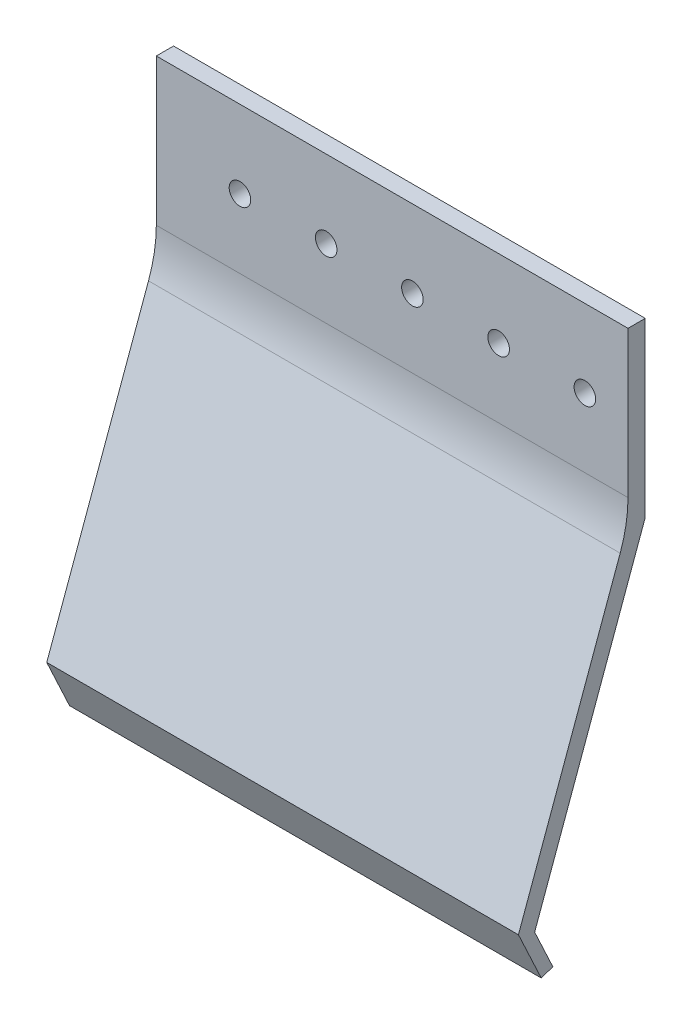
SolidWorks part; units mm, degrees
ref_plane "Front Plane" through (0, 0, 0) normal (0, 0, 1) x (1, 0, 0)
ref_plane "Top Plane" through (0, 0, 0) normal (0, 1, 0) x (1, 0, 0)
ref_plane "Right Plane" through (0, 0, 0) normal (1, 0, 0) x (0, 0, -1)
sketch "Sketch1" plane through (0, 0, 0) normal (0, 0, 1) x (1, 0, 0)
  line L0 (-72.2, 72.2) -> (37.2, 72.2)
  line L5 (-57.2, 57.2) -> (22.2, 57.2)
  line L6 (-57.2, 57.2) -> (-57.2, -22.2)
  line L7 (-57.2, -22.2) -> (22.2, -22.2)
  line L8 (22.2, 57.2) -> (22.2, -22.2)
  line L9 (37.2, 72.2) -> (37.2, -37.2)
  line L10 (-72.2, -37.2) -> (37.2, -37.2)
  line L11 (-72.2, 72.2) -> (-72.2, -37.2)
  circle A0 centre (-52.5, 52.5) radius 1.5
  circle A1 centre (-17.5, 52.5) radius 1.5
  circle A2 centre (17.5, 52.5) radius 1.5
  circle A3 centre (-52.5, 17.5) radius 1.5
  circle A4 centre (-17.5, 17.5) radius 1.5
  circle A5 centre (17.5, 17.5) radius 1.5
  circle A6 centre (17.5, -17.5) radius 1.5
  circle A7 centre (-17.5, -17.5) radius 1.5
  circle A8 centre (-52.8099, -17.8099) radius 1.5
  circle A9 centre (-35, 35) radius 6
  circle A10 centre (0, 35) radius 6
  circle A11 centre (0, 0) radius 6
  circle A12 centre (-35, 0) radius 6
  point P49 (-17.5, 17.5)
  dimension "D1" = 15
  dimension "D2" = 4
extrude "Boss-Extrude1" add sketch "Sketch1" along normal blind 8 contours L8 L5 L6 L7 A12 A11 A10 A9 A8 A7 A6 A5 A4 A3 A2 A1 A0 | L0 L11 L10 L9 L5 L8 L7 L6
sketch "Sketch2" plane through (37.2, 0, 0) normal (1, 0, 0) x (0, 0, -1)
  line L0 (-8, 72.2) -> (-33.6515, 1.7231)
  line L1 (-153.8845, -135.915) -> (25.507, -52.2634) construction
  line L2 (-8, -37.2) -> (0, -37.2) construction
  line L3 (-8, 72.2) -> (-8, 112.2)
  line L4 (-12, 72.9053) -> (-12, 112.2)
  line L5 (-12, 72.9053) -> (-37.4103, 3.0911)
  line L6 (-37.4103, 3.0911) -> (-32.1276, -8.2377)
  line L7 (-33.6515, 1.7231) -> (-29.4253, -7.34)
  line L8 (-32.1276, -8.2377) -> (-29.4253, -7.34)
  line L9 (-12, 112.2) -> (-8, 112.2)
  dimension "D1" = 25
  dimension "D2" = 45
  dimension "D3" = 75
  dimension "D4" = 40
  dimension "D6" = 12.5
  dimension "D7" = 0
  dimension "D8" = 10
  dimension "D5" = 4
extrude "Boss-Extrude2" add sketch "Sketch2" against normal up to surface (109.4 mm away) separate body up to face at (-72.2, 17.5, 4)
fillet "Fillet1" radius 30 1 edges at (-17.5, 72.9053, 12)
sketch "Sketch3" plane through (37.2, 0, 0) normal (1, 0, 0) x (0, 0, -1)
  line L1 (-8, 72.2) -> (0, 72.2)
  line L2 (-8, 72.2) -> (-8, -37.2)
  line L3 (-8, -37.2) -> (0, -37.2)
  line L4 (0, 72.2) -> (0, -37.2)
sketch "Sketch4" plane through (0, 0, 12) normal (0, 0, 1) x (1, 0, 0)
  line L1 (-72.2, 112.2) -> (37.2, 112.2) construction
  line L2 (-17.5, 112.2) -> (-17.5, 101.2893) construction
  circle A5 centre (-52.8, 94.2) radius 2.5
  circle A6 centre (-32.8, 94.2) radius 2.5
  circle A7 centre (-12.8, 94.2) radius 2.5
  circle A8 centre (7.2, 94.2) radius 2.5
  circle A9 centre (27.2, 94.2) radius 2.5
sketch "Sketch5" plane through (37.2, 0, 0) normal (1, 0, 0) x (0, 0, -1)
  line L1 (0, -37.2) -> (-8, -37.2)
  line L2 (0, -37.2) -> (0, 112.2)
  line L3 (0, 112.2) -> (-8, 112.2)
  line L4 (-8, -37.2) -> (-8, 112.2)
extrude "Boss-Extrude3" add sketch "Sketch5" against normal up to surface (109.4 mm away) up to face at (-72.2, 17.5, 4)
extrude "Cut-Extrude4" cut sketch "Sketch3" against normal blind 135
sketch "Sketch7" plane through (37.2, 0, 0) normal (1, 0, 0) x (0, 0, -1)
  line L1 (-8, 72.2) -> (0, 72.2)
  line L2 (-8, 72.2) -> (-8, 112.2)
  line L3 (-8, 112.2) -> (0, 112.2)
  line L4 (0, 72.2) -> (0, 112.2)
extrude "Cut-Extrude5" cut sketch "Sketch7" against normal blind 135
extrude "Cut-Extrude6" cut sketch "Sketch4" against normal blind 10
